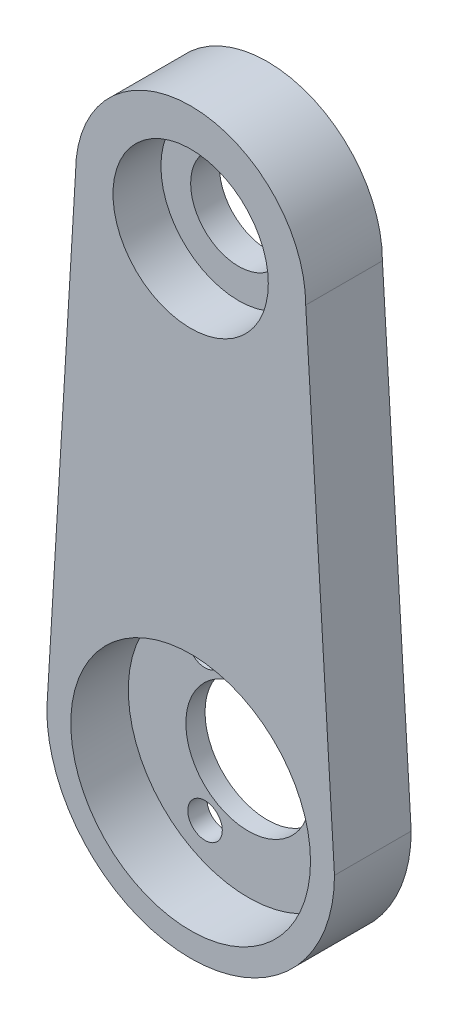
SolidWorks part; units mm, degrees
ref_plane "Plan de face" through (0, 0, 0) normal (0, 0, 1) x (1, 0, 0)
ref_plane "Plan de dessus" through (0, 0, 0) normal (0, 1, 0) x (1, 0, 0)
ref_plane "Plan de droite" through (0, 0, 0) normal (1, 0, 0) x (0, 0, -1)
sketch "Esquisse1" plane through (0, 0, 0) normal (0, 0, 1) x (1, 0, 0)
  line L0 (-16.3093, 0) -> (24.5372, 0) construction
  line L1 (12, 0) -> (15, -50)
  line L2 (-12, 0) -> (-15, -50)
  line L3 (-15, -50) -> (15, -50) construction
  line L4 (0, 0) -> (0, -50) construction
  arc A0 (-12, 0) -> (12, 0) centre (0, 0) cw
  arc A1 (-15, -50) -> (15, -50) centre (0, -50) ccw
  dimension "D1" = 12
  dimension "D2" = 15
  dimension "D3" = 50
extrude "Boss.-Extru.1" add sketch "Esquisse1" along normal blind 8
sketch "Esquisse2" plane through (0, 0, 8) normal (0, 0, 1) x (1, 0, 0)
  line L0 (0, 0) -> (0, -65) construction
  line L1 (15, -50) -> (-15, -50) construction
  circle A0 centre (0, -50) radius 6.5
  arc A1 (-15, -50) -> (15, -50) centre (0, -50) ccw construction
extrude "Enlèv. mat.-Extru.1" cut sketch "Esquisse2" against normal blind 10
sketch "Esquisse3" plane through (0, 0, 8) normal (0, 0, 1) x (1, 0, 0)
  line L0 (0, -50) -> (0, 0) construction
  line L1 (0, -50) -> (9, -50) construction
  line L2 (0, -50) -> (-4.5, -42.2058) construction
  line L3 (0, -50) -> (-4.5, -57.7942) construction
  line L4 (0, -50) -> (-9, -50) construction
  line L5 (-9, -50) -> (0, -50) construction
  circle A0 centre (-4.5, -57.7942) radius 1.8
  circle A1 centre (-4.5, -42.2058) radius 1.8
  circle A2 centre (9, -50) radius 1.8
  dimension "D1" = 120
  dimension "D2" = 120
extrude "Enlèv. mat.-Extru.2" cut sketch "Esquisse3" against normal blind 10
ref_plane "Plan1" through (0, 10, 0) normal (0, 1, 0) x (1, 0, 0)
sketch "Esquisse5" plane through (0, 0, 8) normal (0, 0, 1) x (1, 0, 0)
  circle A0 centre (0, -50) radius 12.5
  dimension "D1" = 25
extrude "Enlèv. mat.-Extru.5" cut sketch "Esquisse5" against normal blind 6
sketch "Esquisse19" plane through (0, 0, 8) normal (0, 0, 1) x (1, 0, 0)
  circle A0 centre (0, 0) radius 8.1
extrude "Enlèv. mat.-Extru.6" cut sketch "Esquisse19" against normal blind 10 contours A0
sketch "Esquisse21" plane through (0, 0, 0) normal (0, 0, -1) x (-1, 0, 0)
  line L0 (-12, 0) -> (-15, -50)
  line L1 (12, 0) -> (15, -50)
  circle A0 centre (0, 0) radius 12
  circle A1 centre (0, -50) radius 15
sketch "Esquisse22" plane through (0, 0, 0) normal (0, 0, -1) x (-1, 0, 0)
  circle A0 centre (0, 0) radius 8.1
  circle A1 centre (0, 0) radius 5
extrude "Boss.-Extru.2" add sketch "Esquisse22" against normal blind 3
